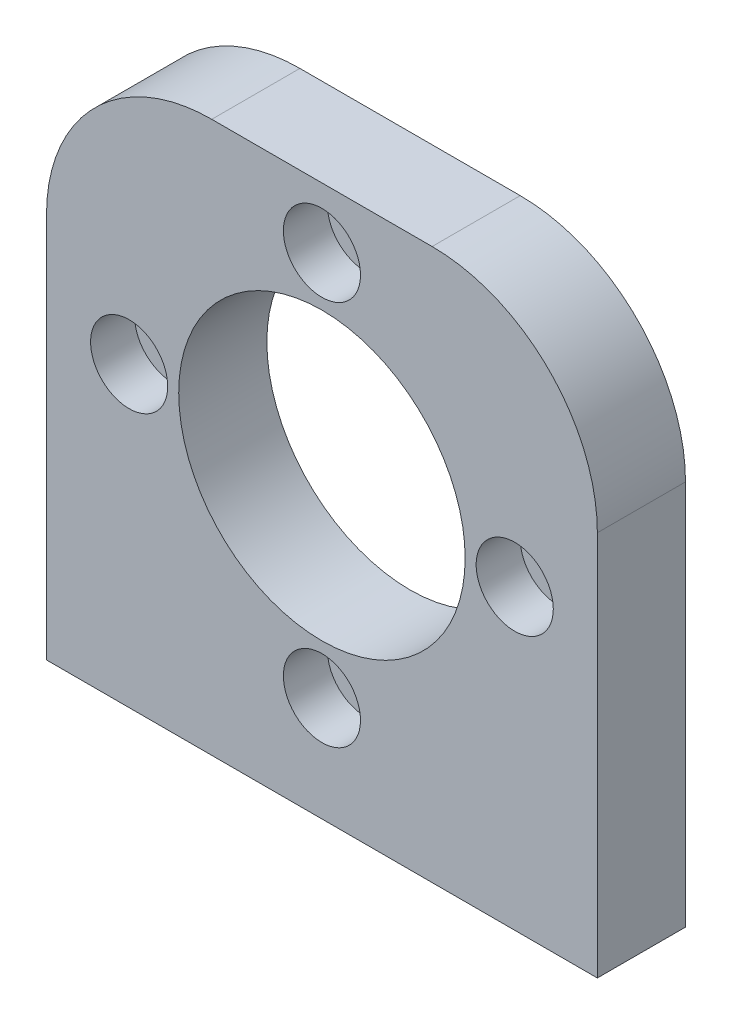
SolidWorks part; units mm, degrees
ref_plane "前视基准面" through (0, 0, 0) normal (0, 0, 1) x (1, 0, 0)
ref_plane "上视基准面" through (0, 0, 0) normal (0, 1, 0) x (1, 0, 0)
ref_plane "右视基准面" through (0, 0, 0) normal (1, 0, 0) x (0, 0, -1)
ref_plane "基准面4" through (0, 0, 8) normal (0, 0, 1) x (1, 0, 0)
sketch "草图1" plane through (0, 0, 8) normal (0, 0, 1) x (1, 0, 0)
  line L0 (14.0626, 53.8265) -> (14.0626, 3.8265)
  line L1 (14.0626, 3.8265) -> (64.0626, 3.8265)
  line L2 (64.0626, 3.8265) -> (64.0626, 53.8265)
  line L3 (64.0626, 53.8265) -> (14.0626, 53.8265)
extrude "凸台-拉伸1" add sketch "草图1" against normal blind 8
hole_wizard "M22 间隙孔1" positions "草图3" profile "草图2" hole size "M22" standard "ANSI Metric"
sketch "草图3" plane through (0, 0, 0) normal (0, 0, -1) x (-1, 0, 0)
  point P0 (-39.0626, 30.8294)
sketch "草图2" plane through (39.0626, 30.8294, 0) normal (1, 0, 0) x (0, 1, 0)
  line L0 (0, 0) -> (0, 8)
  line L1 (0, 8) -> (13, 8)
  line L2 (13, 8) -> (13, 0)
  line L5 (13, 0) -> (0, 0)
  line L11 (0, -6.35) -> (0, 107.95) construction
  dimension "通孔孔直径" = 26
  dimension "通孔孔深度" = 8
hole_wizard "M3.5 六角头机械螺钉的柱形沉头孔1" positions "草图5" profile "草图4" counterbore size "M3.5" standard "ANSI Metric"
sketch "草图5" plane through (0, 0, 8) normal (0, 0, 1) x (1, 0, 0)
  point P0 (39.0626, 13.3294)
  point P1 (39.0626, 48.3294)
  point P2 (56.5626, 30.8294)
  point P3 (21.5626, 30.8294)
sketch "草图4" plane through (39.0626, 13.3294, 8) normal (1, 0, 0) x (0, -1, 0)
  line L0 (0, 0) -> (0, 8)
  line L1 (0, 8) -> (2, 8)
  line L3 (2, 8) -> (2, 4)
  line L4 (2, 4) -> (3.5, 4)
  line L5 (3.5, 4) -> (3.5, 0)
  line L7 (3.5, 0) -> (0, 0)
  line L11 (0, -6.35) -> (0, 107.95) construction
  dimension "通孔孔直径" = 4
  dimension "通孔孔深度" = 8
  dimension "柱形沉头孔直径" = 7
  dimension "柱形沉头孔深度" = 4
hole_wizard "Ø4.2 (4.2) 直径孔1" positions "草图7" profile "草图6" hole size "Ø4.2" standard "ANSI Metric"
sketch "草图7" plane through (0, 3.8265, 0) normal (0, -1, 0) x (-1, 0, 0)
  point P0 (-24.0626, -4)
  point P1 (-54.0626, -4)
sketch "草图6" plane through (24.0626, 3.8265, 4) normal (1, 0, 0) x (0, 0, -1)
  line L0 (0, 0) -> (0, 13.6618)
  line L1 (0, 13.6618) -> (2.1, 12.4)
  line L2 (2.1, 12.4) -> (2.1, 0)
  line L5 (2.1, 0) -> (0, 0)
  line L10 (0, 13.6618) -> (-2.1, 12.4) construction
  line L11 (0, -6.35) -> (0, 107.95) construction
  dimension "孔直径" = 4.2
  dimension "孔深度" = 12.4
  dimension "导头角度" = 118
fillet "圆角1" radius 15 2 edges at (64.0626, 53.8265, 4) (14.0626, 53.8265, 4)
